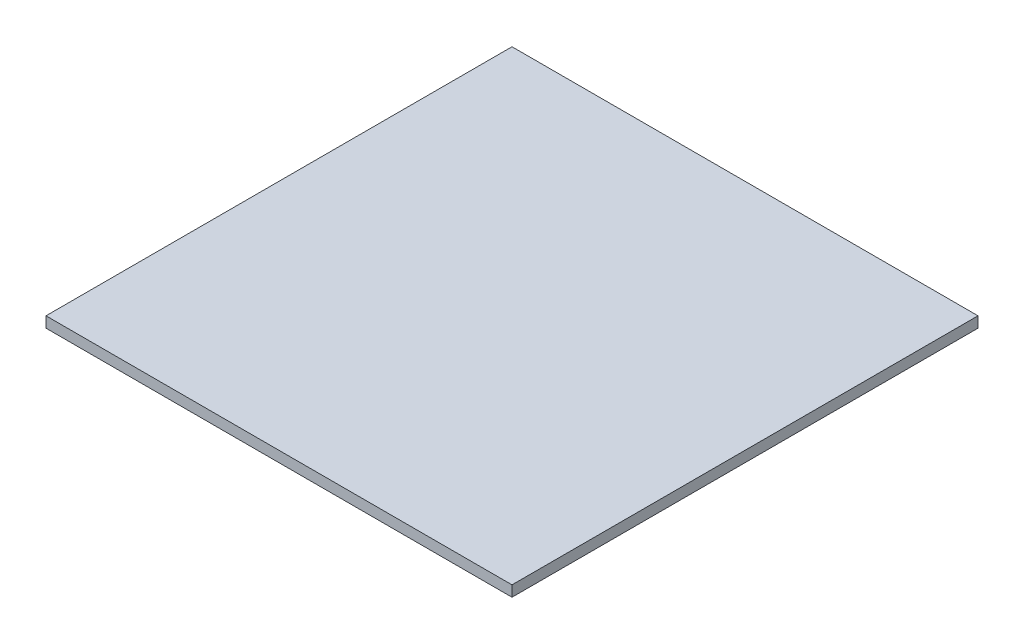
SolidWorks part; units mm, degrees
ref_plane "Front Plane" through (0, 0, 0) normal (0, 0, 1) x (1, 0, 0)
ref_plane "Top Plane" through (0, 0, 0) normal (0, 1, 0) x (1, 0, 0)
ref_plane "Right Plane" through (0, 0, 0) normal (1, 0, 0) x (0, 0, -1)
sketch "Sketch1" plane through (0, 0, 0) normal (0, 1, 0) x (1, 0, 0)
  line L1 (-130, -130) -> (130, -130)
  line L2 (-130, -130) -> (-130, 130)
  line L3 (-130, 130) -> (130, 130)
  line L4 (130, -130) -> (130, 130)
  line L5 (-130, -130) -> (130, 130) construction
  line L6 (-130, 130) -> (130, -130) construction
  point P0 (0, 0)
  dimension "D1" = 260
  dimension "D2" = 260
extrude "Boss-Extrude1" add sketch "Sketch1" along normal blind 6
